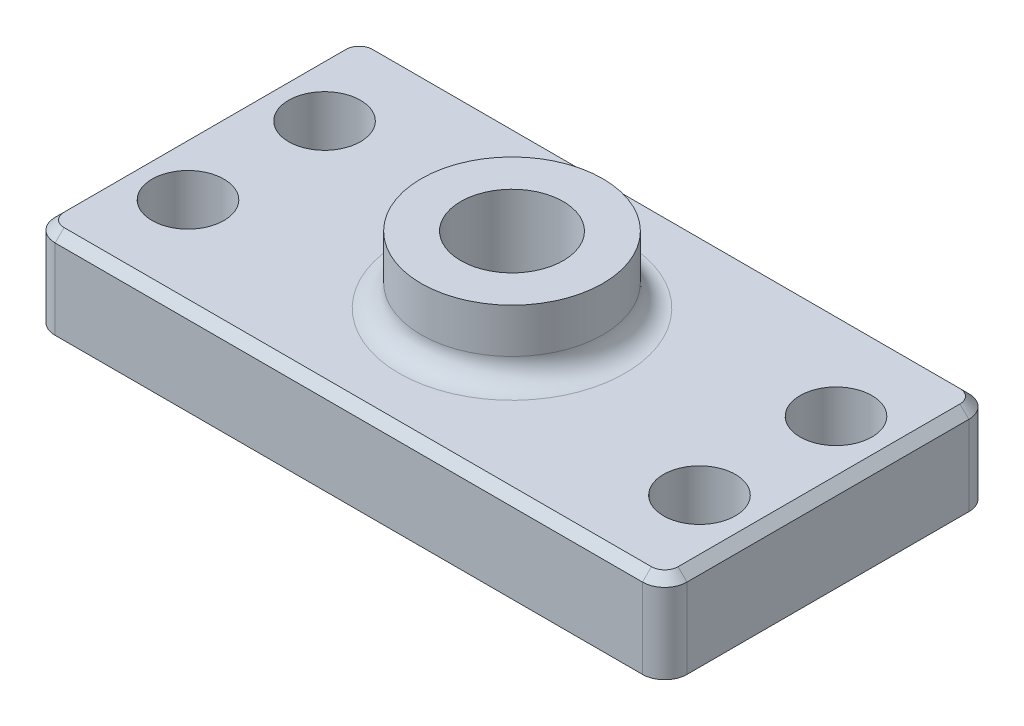
SolidWorks part; units mm, degrees
ref_plane "Front Plane" through (0, 0, 0) normal (0, 0, 1) x (1, 0, 0)
ref_plane "Top Plane" through (0, 0, 0) normal (0, 1, 0) x (1, 0, 0)
ref_plane "Right Plane" through (0, 0, 0) normal (1, 0, 0) x (0, 0, -1)
sketch "Sketch1" plane through (0, 0, 0) normal (0, 1, 0) x (1, 0, 0)
  line L0 (0, 0) -> (0, 59.5172) construction
  line L1 (-90.2677, -46.6218) -> (90.2677, -46.6218)
  line L2 (-90.2677, -46.6218) -> (-90.2677, 46.6218)
  line L3 (-90.2677, 46.6218) -> (90.2677, 46.6218)
  line L4 (90.2677, -46.6218) -> (90.2677, 46.6218)
  line L5 (-90.2677, -46.6218) -> (90.2677, 46.6218) construction
  line L6 (-90.2677, 46.6218) -> (90.2677, -46.6218) construction
  line L7 (0, 0) -> (-85.3079, 0) construction
  line L8 (-90.2677, -46.6218) -> (-90.2677, 46.6218)
  line L9 (90.2677, -46.6218) -> (90.2677, 46.6218)
  circle A0 centre (-73.0738, 19.5084) radius 10.2715
  circle A1 centre (73.0738, 19.5084) radius 10.2715
  circle A2 centre (73.0738, -19.5084) radius 10.2715
  circle A3 centre (-73.0738, -19.5084) radius 10.2715
  point P0 (0, 0)
extrude "Boss-Extrude1" add sketch "Sketch1" along normal blind 25.4 contours L1 L4 L3 L2 A1 A0 A2 A3
sketch "Sketch2" plane through (0, 25.4, 0) normal (0, 1, 0) x (1, 0, 0)
  circle A0 centre (0, 0) radius 25.9448
extrude "Boss-Extrude2" add sketch "Sketch2" along normal blind 19.05
sketch "Sketch3" plane through (0, 44.45, 0) normal (0, 1, 0) x (1, 0, 0)
  circle A0 centre (0, 0) radius 14.648
extrude "Cut-Extrude1" cut sketch "Sketch3" against normal through all
fillet "Fillet2" radius 6.35 5 edges at (-90.2677, 12.7, -46.6218) (90.2677, 12.7, -46.6218) (90.2677, 12.7, 46.6218) (0, 25.4, 25.9448) (-90.2677, 12.7, 46.6218)
chamfer "Chamfer1" distance 2.54 angle 45 8 edges at (0, 25.4, -46.6218) (-88.4078, 25.4, -44.7619) (88.4078, 25.4, -44.7619) (-90.2677, 25.4, 0) (90.2677, 25.4, 0) (-88.4078, 25.4, 44.7619) (88.4078, 25.4, 44.7619) (0, 25.4, 46.6218)
